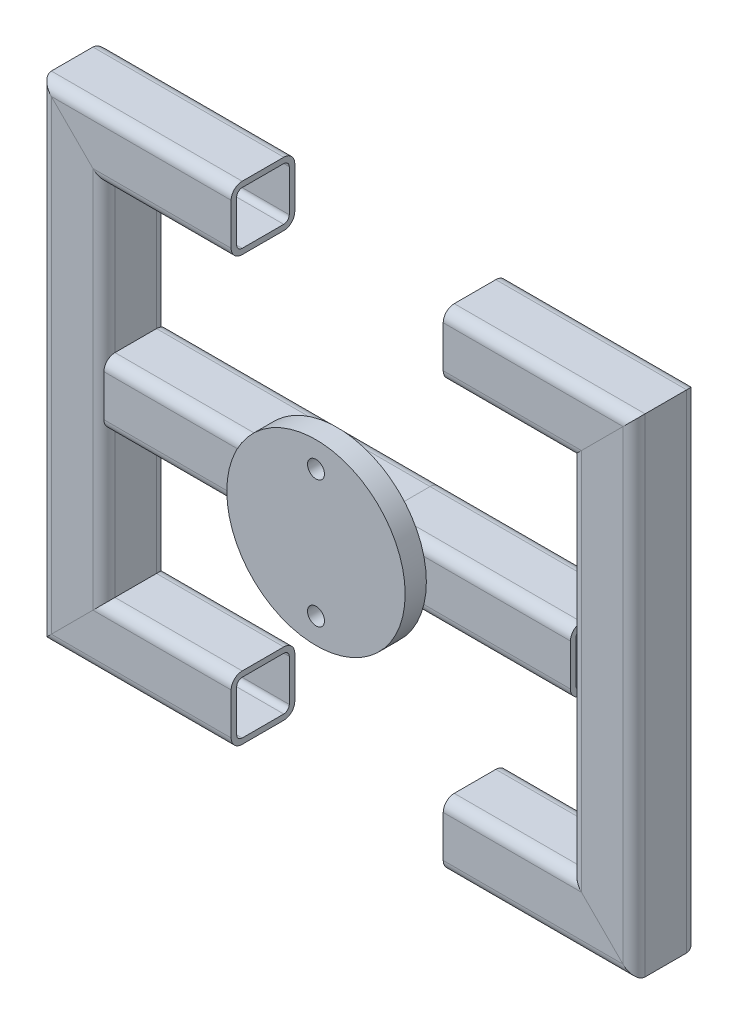
SolidWorks part; units mm, degrees
other "DetailItem1"
other "DetailItem2"
other "DetailItem3"
other "DetailItem4"
other "DetailItem5"
other "DetailItem6"
other "DetailItem7"
other "DetailItem8"
other "DetailItem9"
other "DetailItem10"
other "DetailItem11"
other "Weld Folder"
other "Weld Bead1"
other "Weld Bead2"
other "Weld Bead3"
other "Weld Bead4"
other "Weld Bead5"
other "Weld Bead6"
other "Weld Bead7"
other "Weld Bead8"
other "Weld Bead9"
other "Weld Bead10"
other "Weld Bead11"
ref_plane "Front Plane" through (0, 0, 0) normal (0, 0, 1) x (1, 0, 0)
ref_plane "Top Plane" through (0, 0, 0) normal (0, 1, 0) x (1, 0, 0)
ref_plane "Right Plane" through (0, 0, 0) normal (1, 0, 0) x (0, 0, -1)
sketch "Sketch1" plane through (0, 0, 0) normal (0, 0, 1) x (1, 0, 0)
  line L0 (-125, 100) -> (-125, -100)
  line L1 (-125, -100) -> (-50, -100)
  line L2 (-125, 100) -> (-50, 100)
  line L3 (50, 100) -> (125, 100)
  line L4 (125, 100) -> (125, -100)
  line L5 (125, -100) -> (50, -100)
  line L6 (-19, 0) -> (-125, 0)
  line L13 (19, 0) -> (125, 0)
  line L14 (19, 0) -> (-19, 0)
  point P6 (0, 0)
  dimension "D1" = 125
  dimension "D2" = 125
  dimension "D3" = 200
  dimension "D4" = 200
  dimension "D5" = 100
  dimension "D6" = 75
  dimension "D7" = 75
  dimension "D8" = 75
  dimension "D9" = 75
  dimension "D10" = 38
  dimension "D11" = 106
  dimension "D12" = 106
  dimension "D13" = 19
  dimension "D14" = 100
other "Square tube 30 X 30 X 2.6(1)"
ref_plane "Plane1" through (-125, 100, 0) normal (1, 0, 0) x (0, 1, 0)
sketch "Sketch16" plane through (-125, 100, 0) normal (1, 0, 0) x (0, 1, 0)
  line L0 (-9.8, -12.4) -> (9.8, -12.4)
  line L1 (-12.4, -9.8) -> (-12.4, 9.8)
  line L2 (9.8, 12.4) -> (-9.8, 12.4)
  line L3 (12.4, 9.8) -> (12.4, -9.8)
  line L4 (-9.8, -15) -> (9.8, -15)
  line L5 (-15, -9.8) -> (-15, 9.8)
  line L6 (9.8, 15) -> (-9.8, 15)
  line L7 (15, 9.8) -> (15, -9.8)
  arc A0 (15, 9.8) -> (9.8, 15) centre (9.8, 9.8) ccw
  arc A1 (9.8, -15) -> (15, -9.8) centre (9.8, -9.8) ccw
  arc A2 (-15, -9.8) -> (-9.8, -15) centre (-9.8, -9.8) ccw
  arc A3 (-9.8, 15) -> (-15, 9.8) centre (-9.8, 9.8) ccw
  arc A4 (-9.8, 12.4) -> (-12.4, 9.8) centre (-9.8, 9.8) ccw
  arc A5 (12.4, 9.8) -> (9.8, 12.4) centre (9.8, 9.8) ccw
  arc A6 (9.8, -12.4) -> (12.4, -9.8) centre (9.8, -9.8) ccw
  arc A7 (-12.4, -9.8) -> (-9.8, -12.4) centre (-9.8, -9.8) ccw
  point P0 (-15, 0)
  point P1 (15, 0)
  point P2 (0, 15)
  point P3 (0, -15)
  point P4 (0, 0)
  point P5 (-15, -15)
  point P6 (15, -15)
  point P7 (15, 15)
  point P8 (-15, 15)
  point P33 (0, 0)
  dimension "D1" = 5.2
  dimension "Thickness" = 2.6
  dimension "V_leg" = 30
sketch "Sketch17" plane through (0, 0, 15) normal (0, 0, 1) x (1, 0, 0)
  circle A1 centre (0, 0) radius 42.055
  dimension "D1" = 84.11
extrude "Boss-Extrude1" add sketch "Sketch17" along normal blind 10 separate body
sketch "Sketch18" plane through (0, 0, 25) normal (0, 0, 1) x (1, 0, 0)
  circle A0 centre (0, 30) radius 4
  circle A1 centre (0, -30) radius 4
  dimension "D1" = 8
  dimension "D2" = 8
extrude "Cut-Extrude1" cut sketch "Sketch18" against normal blind 10
